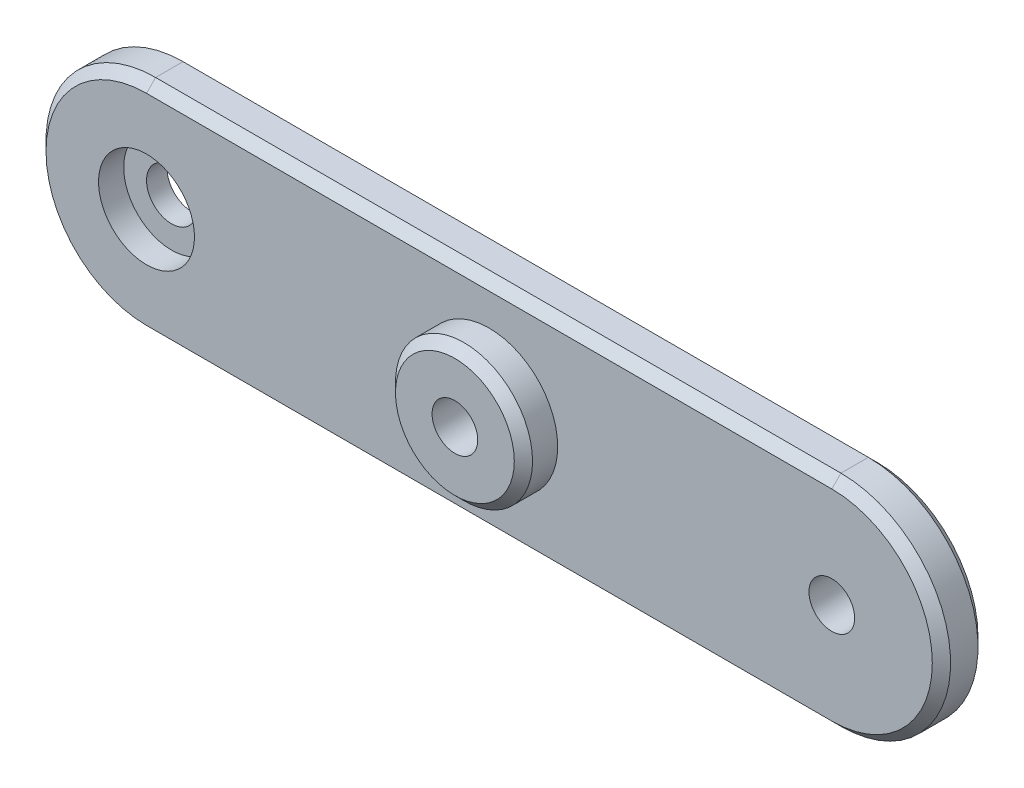
SolidWorks part; units mm, degrees
material "6061-T6 (SS)"
ref_plane "Front Plane" through (0, 0, 0) normal (0, 0, 1) x (1, 0, 0)
ref_plane "Top Plane" through (0, 0, 0) normal (0, 1, 0) x (1, 0, 0)
ref_plane "Right Plane" through (0, 0, 0) normal (1, 0, 0) x (0, 0, -1)
sketch "Sketch2" plane through (0, 0, 0) normal (0, 0, 1) x (1, 0, 0)
  line L0 (-37.5, 0) -> (37.5, 0) construction
  line L1 (-37.5, 12) -> (37.5, 12)
  line L2 (-37.5, -12) -> (37.5, -12)
  arc A0 (-37.5, 12) -> (-37.5, -12) centre (-37.5, 0) ccw
  arc A1 (37.5, -12) -> (37.5, 12) centre (37.5, 0) ccw
  point P2 (0, 0)
  dimension "D1" = 12
  dimension "D2" = 75
extrude "Boss-Extrude1" add sketch "Sketch2" along normal blind 5
sketch "Sketch4" plane through (0, 0, 0) normal (0, 0, 1) x (1, 0, 0)
  circle A0 centre (0, 0) radius 7.5
  dimension "D1" = 15
extrude "Boss-Extrude3" add sketch "Sketch4" along normal blind 8.75
sketch "Sketch5" plane through (0, 0, 8.75) normal (0, 0, 1) x (1, 0, 0)
  circle A0 centre (0, 0) radius 2.5
  dimension "D1" = 5
extrude "Cut-Extrude2" cut sketch "Sketch5" against normal blind 10
hole_wizard "CBORE for M5 SBHCS1" positions "Sketch6" profile "Sketch7" counterbore size "M5" standard "ANSI Metric" end condition through all
sketch "Sketch6" plane through (0, 0, 5) normal (0, 0, 1) x (1, 0, 0)
  point P0 (-37.5, 0)
sketch "Sketch7" plane through (-37.5, 0, 5) normal (1, 0, 0) x (0, -1, 0)
  line L0 (0, 0) -> (0, 5)
  line L1 (0, 5) -> (2.75, 5)
  line L3 (2.75, 5) -> (2.75, 2.75)
  line L4 (2.75, 2.75) -> (5.25, 2.75)
  line L5 (5.25, 2.75) -> (5.25, 0)
  line L7 (5.25, 0) -> (0, 0)
  line L11 (0, -6.35) -> (0, 107.95) construction
  dimension "Thru Hole Dia." = 5.5
  dimension "Thru Hole Depth" = 5
  dimension "C'Bore Dia." = 10.5
  dimension "C'Bore Depth" = 2.75
sketch "Sketch8" plane through (0, 0, 5) normal (0, 0, 1) x (1, 0, 0)
  circle A0 centre (37.5, 0) radius 2.5
  dimension "D1" = 5
extrude "Cut-Extrude3" cut sketch "Sketch8" against normal blind 10
chamfer "Chamfer1" distance 1 angle 45 9 edges at (0, -12, 0) (49.5, 0, 0) (-49.5, 0, 0) (0, 12, 0) (0, -12, 5) (49.5, 0, 5) (-49.5, 0, 5) (0, 12, 5) (7.5, 0, 8.75)
